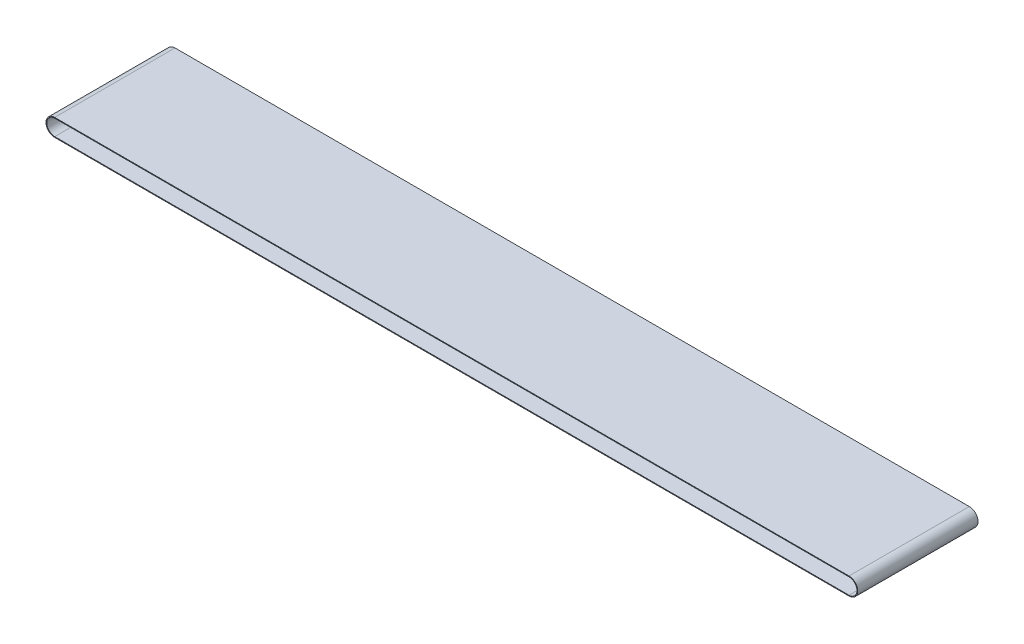
SolidWorks part; units mm, degrees
ref_plane "Front Plane" through (0, 0, 0) normal (0, 0, 1) x (1, 0, 0)
ref_plane "Top Plane" through (0, 0, 0) normal (0, 1, 0) x (1, 0, 0)
ref_plane "Right Plane" through (0, 0, 0) normal (1, 0, 0) x (0, 0, -1)
sketch "Sketch1" plane through (0, 0, 0) normal (0, 0, 1) x (1, 0, 0)
  line L0 (-525, 0) -> (525, 0) construction
  line L1 (-525, 11.5) -> (525, 11.5)
  line L2 (-525, -11.5) -> (525, -11.5)
  line L3 (-525, 10.5) -> (525, 10.5)
  line L4 (-525, -10.5) -> (525, -10.5)
  arc A0 (-525, 11.5) -> (-525, -11.5) centre (-525, 0) ccw
  arc A1 (525, -11.5) -> (525, 11.5) centre (525, 0) ccw
  arc A2 (525, -10.5) -> (525, 10.5) centre (525, 0) ccw
  arc A3 (-525, 10.5) -> (-525, -10.5) centre (-525, 0) ccw
  point P3 (0, 0)
  dimension "D1" = 23
  dimension "D2" = 1050
  dimension "D3" = 1
extrude "Boss-Extrude1" add sketch "Sketch1" along normal mid plane 159
